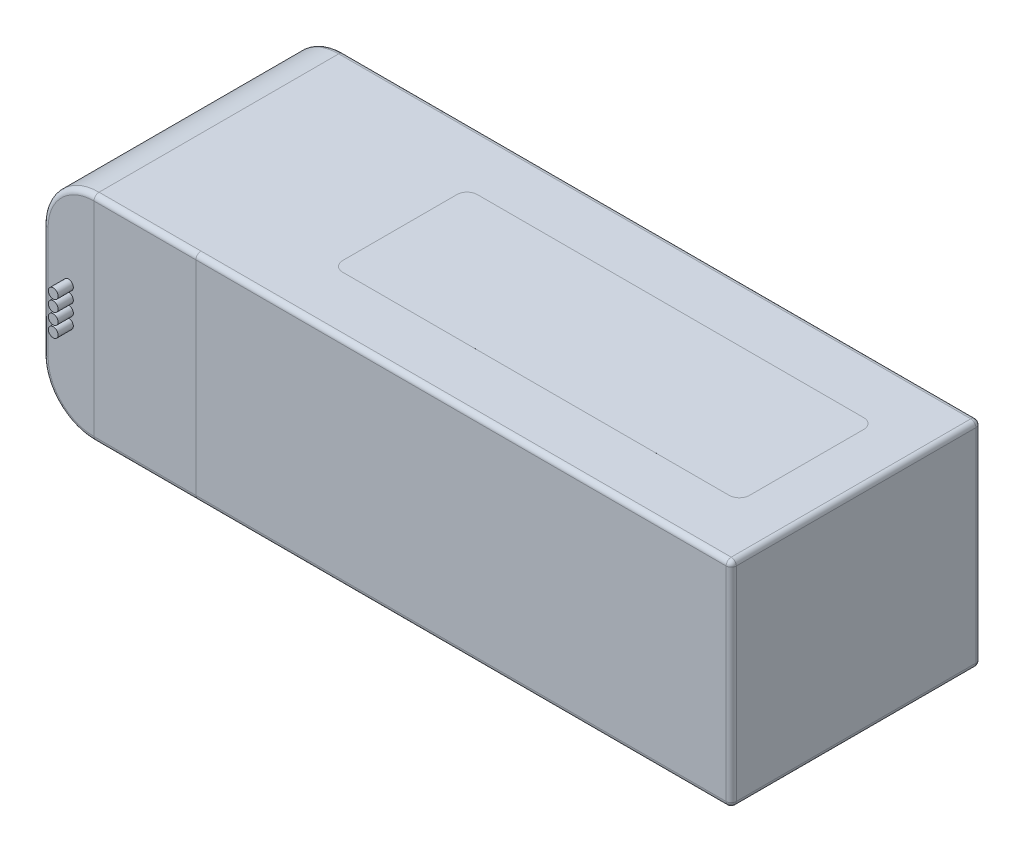
SolidWorks part; units mm, degrees
ref_plane "Plano frontal" through (0, 0, 0) normal (0, 0, 1) x (1, 0, 0)
ref_plane "Plano superior" through (0, 0, 0) normal (0, 1, 0) x (1, 0, 0)
ref_plane "Plano direito" through (0, 0, 0) normal (1, 0, 0) x (0, 0, -1)
sketch "Sketch1" plane through (0, 0, 0) normal (0, 1, 0) x (1, 0, 0)
  line L1 (-67.5, 24.5) -> (67.5, 24.5)
  line L2 (-67.5, 24.5) -> (-67.5, -24.5)
  line L3 (-67.5, -24.5) -> (67.5, -24.5)
  line L4 (67.5, 24.5) -> (67.5, -24.5)
  point P4 (0, 24.5)
  point P6 (-67.5, 0)
  dimension "D1" = 49
  dimension "D2" = 135
extrude "Boss-Extrude1" add sketch "Sketch1" along normal mid plane 42
fillet "Fillet1" radius 10 2 edges at (-67.5, -21, 0) (-67.5, 21, 0)
sketch "Sketch2" plane through (0, 0, -24.5) normal (0, 0, -1) x (-1, 0, 0)
  line L1 (59.5, 1.45) -> (59.5, -1.45) construction
  line L2 (67.5, 11) -> (67.5, -11) construction
  circle A0 centre (59.5, 3.35) radius 1.9
  circle A1 centre (59.5, -3.35) radius 1.9
  point P4 (59.5, 0)
  dimension "D1" = 3.8
  dimension "D2" = 2.9
  dimension "D3" = 8
extrude "Boss-Extrude2" add sketch "Sketch2" along normal blind 5
sketch "Sketch4" plane through (0, 0, 24.5) normal (0, 0, 1) x (1, 0, 0)
  line L0 (-62.5, 4.25) -> (-62.5, -4.25) construction
  line L1 (-67.5, 11) -> (-67.5, -11) construction
  circle A0 centre (-62.5, 3.3) radius 0.95
  circle A1 centre (-62.5, 1.1) radius 0.95
  circle A2 centre (-62.5, -1.1) radius 0.95
  circle A3 centre (-62.5, -3.3) radius 0.95
  point P2 (-62.5, 0)
  dimension "D1" = 1.9
  dimension "D3" = 5
  dimension "D4" = 0.3
  dimension "D2" = 4
extrude "Boss-Extrude3" add sketch "Sketch4" along normal blind 3
sketch "Sketch5" plane through (0, 0, 24.5) normal (0, 0, 1) x (1, 0, 0)
  line L0 (-57.5, -21) -> (67.5, -21) construction
  line L1 (-57.5, 21) -> (-37.5, 21)
  line L2 (-57.5, 21) -> (-57.5, -21)
  line L3 (-57.5, -21) -> (-37.5, -21)
  line L4 (-37.5, 21) -> (-37.5, -21)
  dimension "D1" = 20
extrude "Boss-Extrude4" add sketch "Sketch5" along normal blind 0.0001
mirror "Mirror1" about plane through (0, 0, 0) normal (0, 0, 1) of "Boss-Extrude4" second plane through (0, 0, 0) second plane normal (0, 1, 0)
sketch "Sketch6" plane through (0, 21, 0) normal (0, 1, 0) x (1, 0, 0)
  line L0 (67.5, -24.5) -> (67.5, 24.5) construction
  line L1 (-20, 13.2) -> (55.8, 13.2)
  line L2 (-22, 11.2) -> (-22, -11.2)
  line L3 (-20, -13.2) -> (55.8, -13.2)
  line L4 (57.8, 11.2) -> (57.8, -11.2)
  arc A0 (55.8, 13.2) -> (57.8, 11.2) centre (55.8, 11.2) cw
  arc A1 (55.8, -13.2) -> (57.8, -11.2) centre (55.8, -11.2) ccw
  arc A2 (-22, -11.2) -> (-20, -13.2) centre (-20, -11.2) ccw
  arc A3 (-20, 13.2) -> (-22, 11.2) centre (-20, 11.2) ccw
  point P4 (-22, 0)
  point P10 (57.8, 13.2)
  point P15 (-22, -13.2)
  point P18 (-22, 13.2)
  dimension "D4" = 2
  dimension "D1" = 79.8
  dimension "D2" = 26.4
  dimension "D3" = 9.7
extrude "Boss-Extrude5" add sketch "Sketch6" along normal blind 0.0001
sketch "Sketch7" plane through (0, -21, 0) normal (0, -1, 0) x (1, 0, 0)
  line L0 (67.5, 24.5) -> (67.5, -24.5) construction
  line L1 (-8.1, 12.5) -> (42.8, 12.5)
  line L2 (-10.1, 10.5) -> (-10.1, -10.5)
  line L3 (-8.1, -12.5) -> (42.8, -12.5)
  line L4 (44.8, 10.5) -> (44.8, -10.5)
  arc A0 (42.8, -12.5) -> (44.8, -10.5) centre (42.8, -10.5) ccw
  arc A1 (42.8, 12.5) -> (44.8, 10.5) centre (42.8, 10.5) cw
  arc A2 (-10.1, -10.5) -> (-8.1, -12.5) centre (-8.1, -10.5) ccw
  arc A3 (-8.1, 12.5) -> (-10.1, 10.5) centre (-8.1, 10.5) ccw
  point P12 (-10.1, 0)
  dimension "D1" = 2
  dimension "D2" = 54.9
  dimension "D3" = 25
  dimension "D4" = 22.7
extrude "Boss-Extrude6" add sketch "Sketch7" along normal blind 0.0001
fillet "Fillet7" radius 1 14 edges at (-64.5711, 18.0711, 24.5) (-67.5, 0, 24.5) (-64.5711, 18.0711, -24.5) (-67.5, 0, -24.5) (67.5, 0, 24.5) (67.5, -21, 0) (67.5, 21, 0) (67.5, 0, -24.5) (15, -21, -24.5) (15, 21, -24.5) (15, -21, 24.5) (15, 21, 24.5) (-64.5711, -18.0711, 24.5) (-64.5711, -18.0711, -24.5)
fillet "Fillet8" radius 1 12 edges at (-57.5, 21, 24.0001) (-57.5, -21, 24.0001) (-37.5, -21, 24.0001) (-37.5, 21, 24.0001) (-47.5, -21, 24.5001) (-47.5, 21, 24.5001) (-57.5, -21, -24) (-47.5, 21, -24.5001) (-57.5, 21, -24) (-37.5, 21, -24) (-47.5, -21, -24.5001) (-37.5, -21, -24)
ref_plane "Plane_Mid" through (0, 0, 0) normal (1, 0, 0) x (0, 0, -1)
